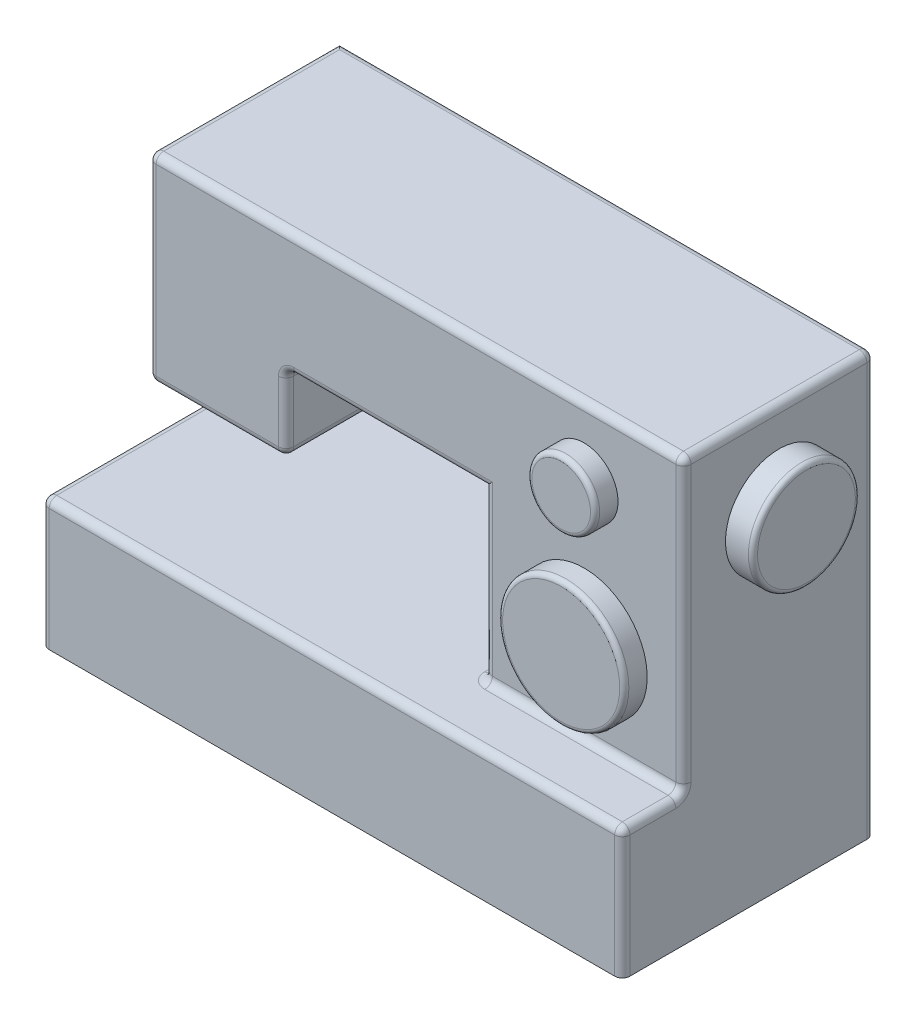
SolidWorks part; units mm, degrees
ref_plane "Front Plane" through (0, 0, 0) normal (0, 0, 1) x (1, 0, 0)
ref_plane "Top Plane" through (0, 0, 0) normal (0, 1, 0) x (1, 0, 0)
ref_plane "Right Plane" through (0, 0, 0) normal (1, 0, 0) x (0, 0, -1)
sketch "Sketch1" plane through (0, 0, 0) normal (0, 1, 0) x (1, 0, 0)
  line L1 (-190, -82.5) -> (190, -82.5)
  line L2 (-190, -82.5) -> (-190, 82.5)
  line L3 (-190, 82.5) -> (190, 82.5)
  line L4 (190, -82.5) -> (190, 82.5)
  line L5 (-190, -82.5) -> (190, 82.5) construction
  line L6 (-190, 82.5) -> (190, -82.5) construction
  point P0 (0, 0)
  dimension "D1" = 380
  dimension "D2" = 165
extrude "Boss-Extrude1" add sketch "Sketch1" along normal blind 85
sketch "Sketch2" plane through (0, 85, 0) normal (0, 1, 0) x (1, 0, 0)
  line L1 (190, 82.5) -> (60, 82.5)
  line L2 (190, 82.5) -> (190, -42.5)
  line L3 (190, -42.5) -> (60, -42.5)
  line L4 (60, 82.5) -> (60, -42.5)
  dimension "D1" = 125
  dimension "D2" = 130
extrude "Boss-Extrude2" add sketch "Sketch2" along normal blind 190
sketch "Sketch3" plane through (0, 0, -82.5) normal (0, 0, -1) x (-1, 0, 0)
  line L0 (-60, 275) -> (160, 275)
  line L1 (160, 275) -> (160, 145)
  line L2 (160, 145) -> (70, 145)
  line L3 (70, 145) -> (70, 195)
  line L4 (70, 195) -> (-60, 195)
  line L5 (-60, 275) -> (-60, 85) construction
  line L6 (-60, 85) -> (190, 85) construction
  line L7 (-190, 275) -> (-190, 0) construction
  line L8 (-60, 195) -> (-60, 275)
  dimension "D1" = 350
  dimension "D2" = 90
  dimension "D3" = 110
  dimension "D4" = 130
extrude "Boss-Extrude3" add sketch "Sketch3" against normal up to surface (125 mm away) up to face at (125, 180, 42.5)
sketch "Sketch5" plane through (190, 0, 0) normal (1, 0, 0) x (0, 0, -1)
  line L0 (-42.5, 275) -> (82.5, 275) construction
  line L1 (-82.5, 0) -> (82.5, 0) construction
  circle A0 centre (20, 215) radius 35
  point P4 (20, 275)
  dimension "D1" = 70
  dimension "D2" = 215
extrude "Boss-Extrude4" add sketch "Sketch5" along normal blind 18
fillet "Fillet1" radius 5 27 edges at (190, 85, 62.5) (-5, 195, -82.5) (-65, 85, -82.5) (190, 42.5, 82.5) (190, 275, -20) (15, 275, -82.5) (190, 137.5, -82.5) (190, 180, 42.5) (-160, 275, -20) (15, 275, 42.5) (-70, 170, -82.5) (-115, 145, -82.5) (-70, 195, -20) (-70, 145, -20) (-160, 210, 42.5) (-160, 145, -20) (-115, 145, 42.5) (-70, 170, 42.5) (-5, 195, 42.5) (60, 140, -82.5) (60, 140, 42.5) (125, 85, 42.5) (60, 85, -20) (0, 85, 82.5) (-190, 85, 0) (-190, 42.5, -82.5) (-190, 42.5, 82.5)
sketch "Sketch6" plane through (0, 0, 42.5) normal (0, 0, 1) x (1, 0, 0)
  line L0 (190, 270) -> (190, 90) construction
  line L3 (-185, 0) -> (185, 0) construction
  circle A0 centre (125, 230) radius 22.2011
  circle A1 centre (125, 140) radius 41.2995
  point P4 (0, 0)
  point P9 (122.5235, 90)
  dimension "D1" = 65
  dimension "D2" = 140
  dimension "D3" = 90
extrude "Boss-Extrude5" add sketch "Sketch6" along normal blind 15
fillet "Fillet2" radius 3 3 edges at (208, 215, -55) (166.2995, 140, 57.5) (147.2011, 230, 57.5)
